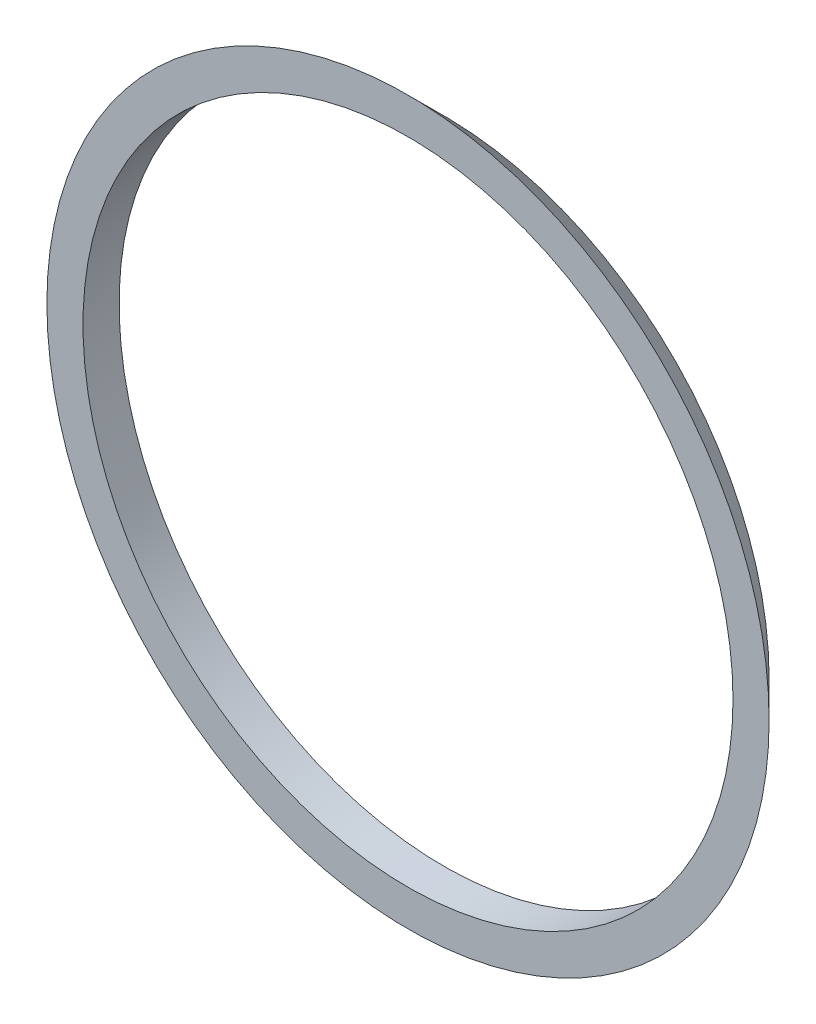
SolidWorks part; units mm, degrees
ref_plane "Front" through (0, 0, 0) normal (0, 0, 1) x (1, 0, 0)
ref_plane "Top" through (0, 0, 0) normal (0, 1, 0) x (1, 0, 0)
ref_plane "Right" through (0, 0, 0) normal (1, 0, 0) x (0, 0, -1)
sketch "Sketch1" plane through (0, 0, 0) normal (1, 0, 0) x (0, 0, -1)
  line L0 (0, 18) -> (0, 20)
  line L1 (0, 20) -> (2, 18)
  line L2 (2, 18) -> (0, 18)
  line L3 (0, 0) -> (2, 0) construction
  point P6 (1, 0)
  dimension "D1" = 18
  dimension "D2" = 2
  dimension "D3" = 2
revolve "Revolve1" add sketch "Sketch1" angle 360 about L3
